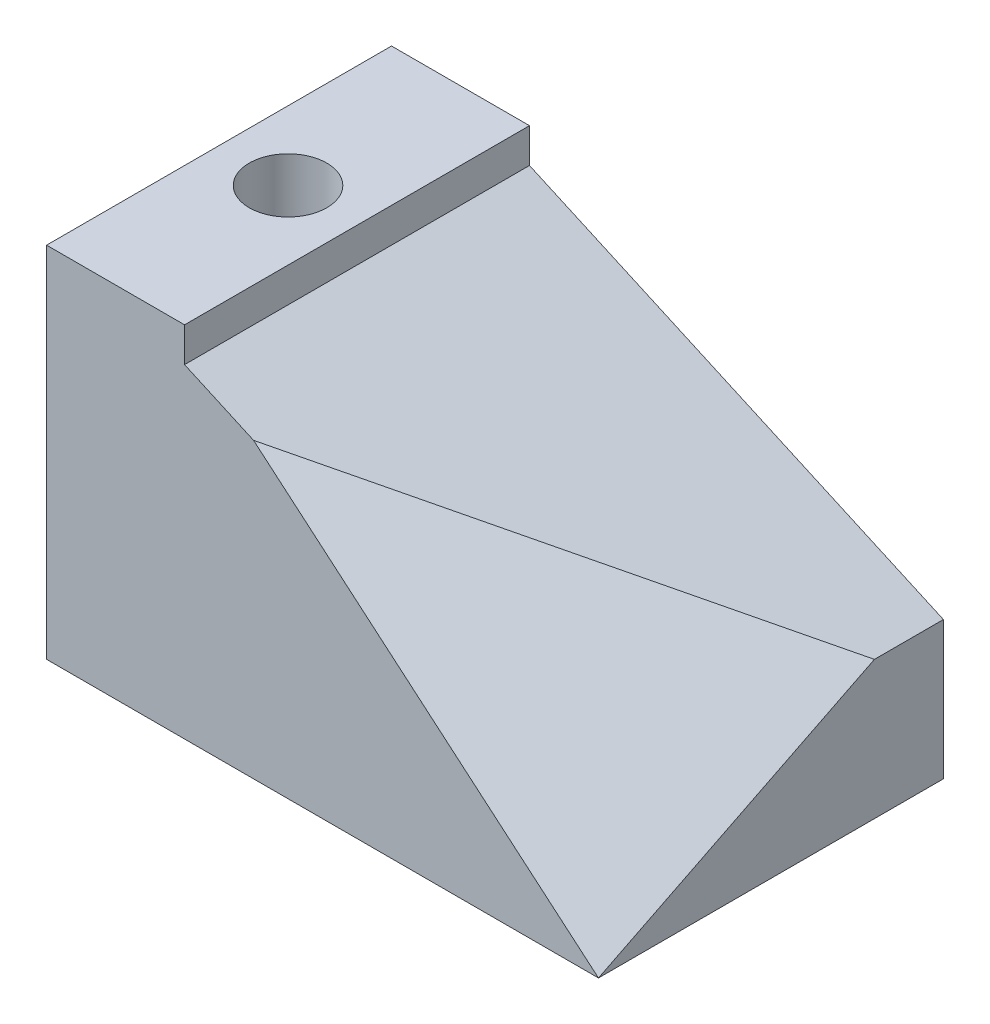
SolidWorks part; units mm, degrees
ref_plane "Front Plane" through (0, 0, 0) normal (0, 0, 1) x (1, 0, 0)
ref_plane "Top Plane" through (0, 0, 0) normal (0, 1, 0) x (1, 0, 0)
ref_plane "Right Plane" through (0, 0, 0) normal (1, 0, 0) x (0, 0, -1)
sketch "Croquis3" plane through (0, 0, 0) normal (0, 0, 1) x (1, 0, 0)
  line L0 (0, 0) -> (101.6, 0)
  line L1 (101.6, 0) -> (101.6, 25.4)
  line L2 (101.6, 25.4) -> (25.4, 59.69)
  line L3 (25.4, 59.69) -> (25.4, 66.04)
  line L4 (25.4, 66.04) -> (0, 66.04)
  line L5 (0, 66.04) -> (0, 0)
  dimension "D1" = 101.6
  dimension "D2" = 25.4
  dimension "D3" = 6.35
  dimension "D4" = 25.4
  dimension "D5" = 66.04
extrude "Saliente-Extruir1" add sketch "Croquis3" along normal blind 63.5
sketch "Croquis4" plane through (0, 66.04, 0) normal (0, 1, 0) x (1, 0, 0)
  line L0 (0, -31.75) -> (25.4, -31.75) construction
  line L1 (0, -63.5) -> (0, 0) construction
  line L2 (25.4, -63.5) -> (25.4, 0) construction
  circle A0 centre (12.7, -31.75) radius 7.1374
  dimension "D1" = 14.2748
extrude "Cortar-Extruir1" cut sketch "Croquis4" against normal blind 38.1
sketch3d "Croquis3D1"
  line L0 (101.6, 0, 63.5) -> (101.6, 25.4, 12.7)
  line L1 (101.6, 25.4, 63.5) -> (101.6, 25.4, 0) construction
  line L2 (38.1, 53.975, 63.5) -> (101.6, 0, 63.5)
  line L3 (101.6, 25.4, 63.5) -> (25.4, 59.69, 63.5) construction
  line L4 (38.1, 53.975, 63.5) -> (101.6, 25.4, 12.7)
  line L5 (0, 66.04, 63.5) -> (0, 0, 63.5) construction
  dimension "D1" = 38.1
  dimension "D2" = 12.7
extrude "Cortar-Extruir2" cut sketch "Croquis3D1" along direction (-0.4104, -0.9119, 0) on the side against the normal through all
